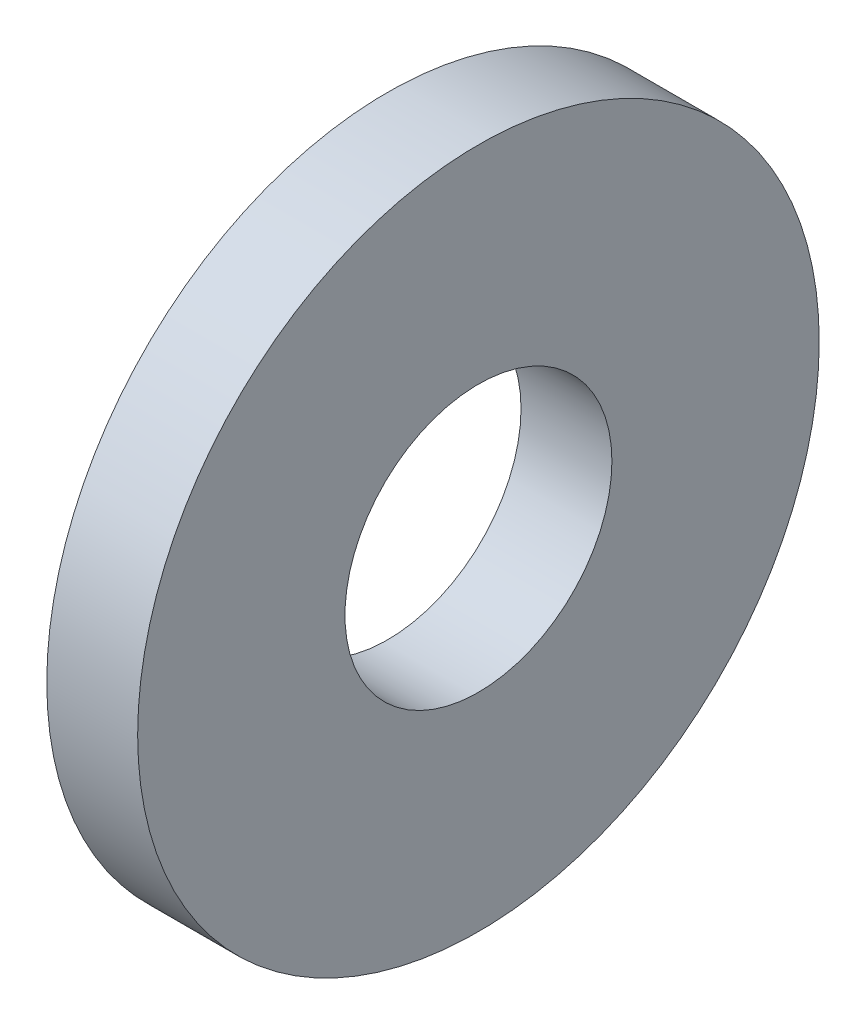
SolidWorks part; units mm, degrees
ref_plane "Plane1" through (0, 0, 0) normal (0, 0, 1) x (1, 0, 0)
ref_plane "Plane2" through (0, 0, 0) normal (0, 1, 0) x (1, 0, 0)
ref_plane "Plane3" through (0, 0, 0) normal (1, 0, 0) x (0, 0, -1)
other "Configuration Table"
sketch "Sketch1" plane through (0, 0, 0) normal (1, 0, 0) x (0, 0, -1)
  circle A0 centre (0, 0) radius 2.35
  circle A1 centre (0, 0) radius 6
  dimension "Insid_dia" = 4.7
  dimension "OutsideDia" = 12
extrude "Base-Extrude" add sketch "Sketch1" along normal blind 1.6
